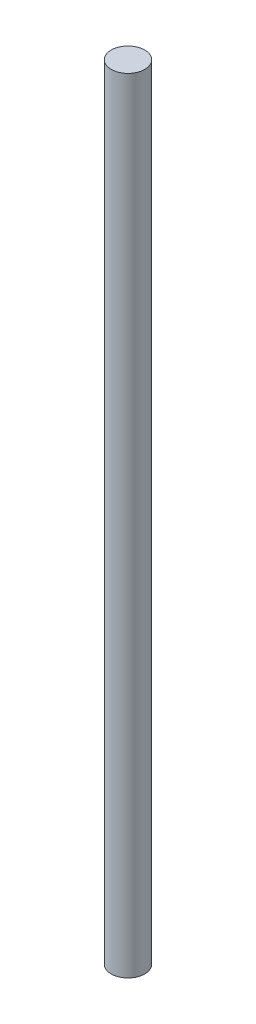
SolidWorks part; units mm, degrees
ref_plane "Alzado" through (0, 0, 0) normal (0, 0, 1) x (1, 0, 0)
ref_plane "Planta" through (0, 0, 0) normal (0, 1, 0) x (1, 0, 0)
ref_plane "Vista lateral" through (0, 0, 0) normal (1, 0, 0) x (0, 0, -1)
sketch "Croquis1" plane through (0, 0, 0) normal (0, 1, 0) x (1, 0, 0)
  circle A0 centre (0, 0) radius 1.5
  dimension "D1" = 3
extrude "Saliente-Extruir1" add sketch "Croquis1" along normal blind 70
